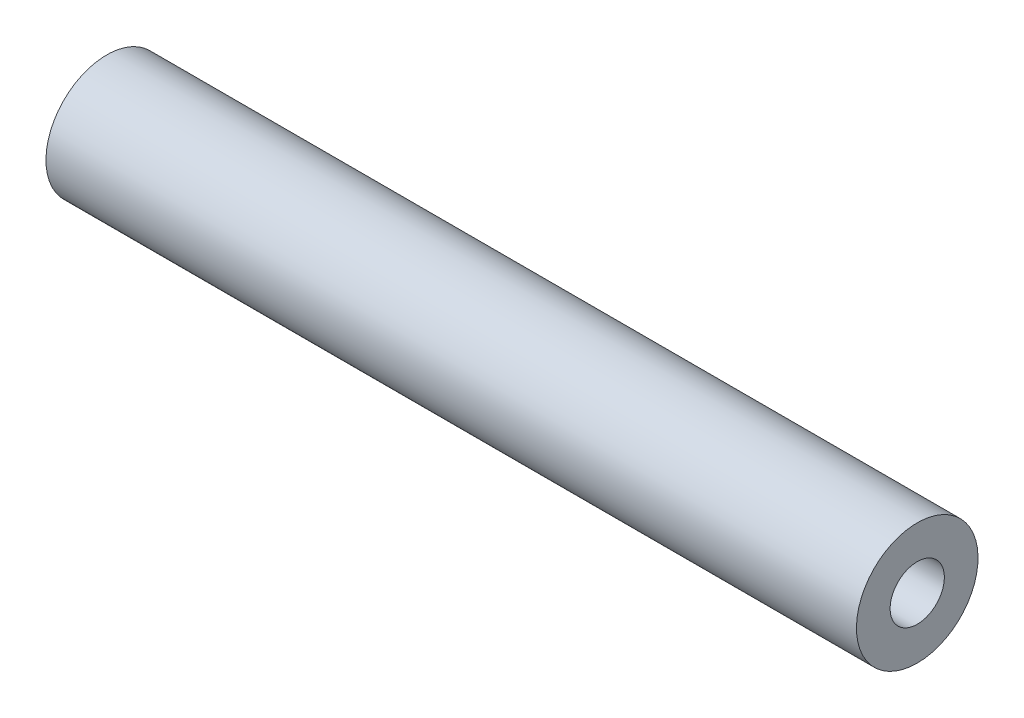
SolidWorks part; units mm, degrees
ref_plane "Front Plane" through (0, 0, 0) normal (0, 0, 1) x (1, 0, 0)
ref_plane "Top Plane" through (0, 0, 0) normal (0, 1, 0) x (1, 0, 0)
ref_plane "Right Plane" through (0, 0, 0) normal (1, 0, 0) x (0, 0, -1)
sketch "Sketch1" plane through (0, 0, 0) normal (0, 0, 1) x (1, 0, 0)
  line L1 (0, 0) -> (50.8, 0) construction
  line L2 (0, 0) -> (0, 3.81)
  line L3 (0, 3.81) -> (50.8, 3.81)
  line L4 (50.8, 0) -> (50.8, 3.81)
  line L5 (25.4, 3.81) -> (25.4, 0) construction
  line L7 (12.9075, 0) -> (0, 0)
  line L8 (37.8925, 0) -> (50.8, 0)
  line L11 (12.9075, 0) -> (37.8925, 0)
  point P208 (25.4, 1.5)
  dimension "D1" = 50.8
  dimension "D2" = 3.81
revolve "Revolve1" add sketch "Sketch1" angle 360 about L3
sketch "Sketch4" plane through (0, 0, 0) normal (-1, 0, 0) x (0, 0, 1)
  point P0 (0, 3.81)
hole_wizard "M3 Clearance Hole1" positions "Sketch5" profile "Sketch6" hole size "M3" standard "ANSI Metric"
sketch "Sketch5" plane through (0, 0, 0) normal (-1, 0, 0) x (0, 0, 1)
  point P0 (0, 3.81)
sketch "Sketch6" plane through (0, 3.81, 0) normal (0, 1, 0) x (0, 0, 1)
  line L0 (0, 0) -> (0, 7.3715)
  line L1 (0, 7.3715) -> (1.7, 6.35)
  line L2 (1.7, 6.35) -> (1.7, 0)
  line L5 (1.7, 0) -> (0, 0)
  line L10 (0, 7.3715) -> (-1.7, 6.35) construction
  line L11 (0, -6.35) -> (0, 107.95) construction
  dimension "Hole Dia." = 3.4
  dimension "Hole Depth" = 6.35
  dimension "Drill Angle" = 118
ref_plane "Plane1" through (25.4, 0, 0) normal (-1, 0, 0) x (0, 0, 1)
mirror "Mirror1" about plane through (25.4, 0, 0) normal (-1, 0, 0) of "M3 Clearance Hole1"
equation "\"arm spacing\"= 2"
equation "\"D1@Sketch1\"=\"arm spacing\""
equation "\"D2@Sketch1\"=\"roller diameter\"/2"
equation "\"symbol room\"= ( ( 35 / 2 ) - 6.5 )"
equation "\"roller diameter\"= .3"
